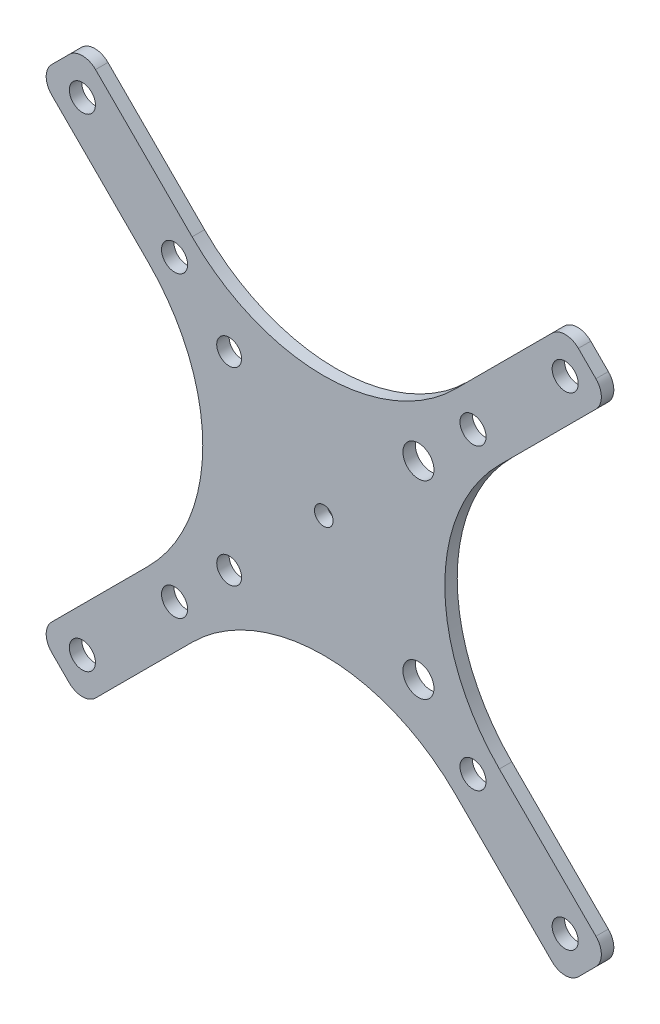
SolidWorks part; units mm, degrees
ref_plane "Alzado" through (0, 0, 0) normal (0, 0, 1) x (1, 0, 0)
ref_plane "Planta" through (0, 0, 0) normal (0, 1, 0) x (1, 0, 0)
ref_plane "Vista lateral" through (0, 0, 0) normal (1, 0, 0) x (0, 0, -1)
sketch "Croquis1" plane through (0, 0, 0) normal (0, 0, 1) x (1, 0, 0)
  line L0 (0, 0) -> (27.8544, 27.8544) construction
  line L1 (0, 0) -> (-42.4264, 42.4264) construction
  line L2 (-31.0962, 38.1673) -> (-21.2132, 28.2843)
  line L3 (15.25, -15.25) -> (-15.25, -15.25) construction
  line L4 (15.25, -15.25) -> (15.25, 15.25) construction
  line L5 (15.25, 15.25) -> (-15.25, 15.25) construction
  line L6 (-15.25, -15.25) -> (-15.25, 15.25) construction
  line L7 (15.25, -15.25) -> (-15.25, 15.25) construction
  line L8 (15.25, 15.25) -> (-15.25, -15.25) construction
  line L9 (21.2132, 28.2843) -> (31.0962, 38.1673)
  line L10 (-42.4264, 42.4264) -> (-38.8909, 45.9619)
  line L11 (-38.8909, 45.9619) -> (-31.0962, 38.1673)
  line L13 (-42.4264, 42.4264) -> (-45.9619, 38.8909)
  line L14 (-45.9619, 38.8909) -> (-38.1673, 31.0962)
  line L16 (38.8909, 45.9619) -> (31.0962, 38.1673)
  line L17 (42.4264, 42.4264) -> (38.8909, 45.9619)
  line L18 (42.4264, 42.4264) -> (45.9619, 38.8909)
  line L19 (-45.9619, -38.8909) -> (-38.1673, -31.0962)
  line L20 (0, 0) -> (-15.25, 0) construction
  line L21 (45.9619, 38.8909) -> (38.1673, 31.0962)
  line L22 (42.4264, -42.4264) -> (45.9619, -38.8909)
  line L23 (42.4264, -42.4264) -> (38.8909, -45.9619)
  line L24 (38.8909, -45.9619) -> (31.0962, -38.1673)
  line L27 (-38.8909, -45.9619) -> (-31.0962, -38.1673)
  line L28 (-42.4264, -42.4264) -> (-38.8909, -45.9619)
  line L29 (-42.4264, -42.4264) -> (-45.9619, -38.8909)
  line L30 (45.9619, -38.8909) -> (38.1673, -31.0962)
  line L31 (-31.0962, -38.1673) -> (-21.2132, -28.2843)
  line L32 (21.2132, -28.2843) -> (31.0962, -38.1673)
  line L33 (-38.1673, 31.0962) -> (-28.2843, 21.2132)
  line L34 (-28.2843, -21.2132) -> (-38.1673, -31.0962)
  line L35 (38.1673, 31.0962) -> (28.2843, 21.2132)
  line L36 (28.2843, -21.2132) -> (38.1673, -31.0962)
  circle A0 centre (-15.25, 15.25) radius 2
  circle A1 centre (-24.0416, 24.0416) radius 2.1
  circle A2 centre (-38.8909, 38.8909) radius 2.1
  circle A5 centre (38.8909, 38.8909) radius 2.1
  circle A6 centre (24.0416, 24.0416) radius 2.1
  circle A7 centre (15.25, 15.25) radius 2.5
  circle A8 centre (15.25, -15.25) radius 2.5
  circle A9 centre (24.0416, -24.0416) radius 2.1
  circle A10 centre (38.8909, -38.8909) radius 2.1
  circle A12 centre (-15.25, -15.25) radius 2
  circle A13 centre (-24.0416, -24.0416) radius 2.1
  circle A14 centre (-38.8909, -38.8909) radius 2.1
  circle A18 centre (0, 0) radius 1.5
  circle A20 centre (-16, -30) radius 3 construction
  circle A21 centre (-16, 30) radius 3 construction
  circle A24 centre (16, -30) radius 3 construction
  circle A25 centre (16, 30) radius 3 construction
  arc A91 (-21.2132, 28.2843) -> (21.2132, 28.2843) centre (0, 49.4975) ccw
  arc A92 (-21.2132, -28.2843) -> (21.2132, -28.2843) centre (0, -49.4975) cw
  arc A93 (-28.2843, 21.2132) -> (-28.2843, -21.2132) centre (-49.4975, 0) cw
  arc A94 (28.2843, 21.2132) -> (28.2843, -21.2132) centre (49.4975, 0) ccw
  point P35 (-34.9935, 42.0646)
  point P37 (44.1942, 40.6586)
  point P45 (44.1942, -40.6586)
  point P51 (-7.0711, 0)
  point P61 (-34.9935, -42.0646)
  dimension "D2" = 4
  dimension "D4" = 5
  dimension "D11" = 4.2
  dimension "D3" = 30
  dimension "D6" = 30
  dimension "D1" = 30.5
  dimension "D5" = 21
  dimension "D7" = 5
  dimension "D9" = 5
extrude "Saliente-Extruir1" add sketch "Croquis1" along normal blind 2
fillet "Redondeo3" radius 3 8 edges at (-45.9619, 38.8909, 1) (-38.8909, 45.9619, 1) (38.8909, 45.9619, 1) (45.9619, 38.8909, 1) (45.9619, -38.8909, 1) (38.8909, -45.9619, 1) (-45.9619, -38.8909, 1) (-38.8909, -45.9619, 1)
